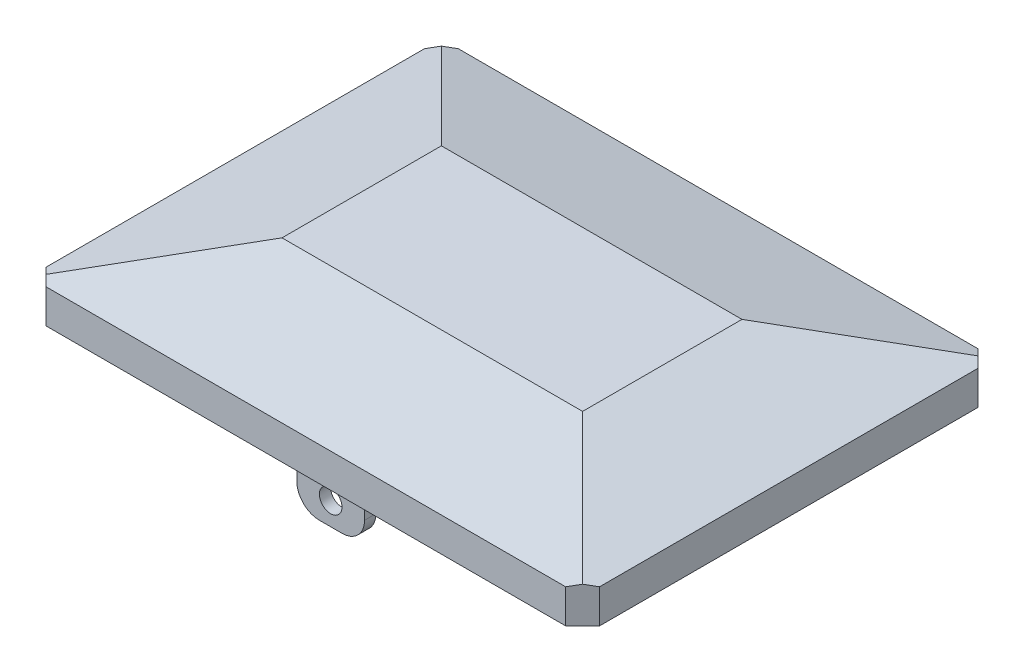
SolidWorks part; units mm, degrees
material "ABS PC"
ref_plane "Front Plane" through (0, 0, 0) normal (0, 0, 1) x (1, 0, 0)
ref_plane "Top Plane" through (0, 0, 0) normal (0, 1, 0) x (1, 0, 0)
ref_plane "Right Plane" through (0, 0, 0) normal (1, 0, 0) x (0, 0, -1)
sketch "Sketch1" plane through (0, 0, 0) normal (0, 1, 0) x (1, 0, 0)
  line L1 (-12.25, 9.125) -> (12.25, 9.125)
  line L2 (-12.25, 9.125) -> (-12.25, -9.125)
  line L3 (-12.25, -9.125) -> (12.25, -9.125)
  line L4 (12.25, 9.125) -> (12.25, -9.125)
  line L5 (-12.25, 9.125) -> (12.25, -9.125) construction
  line L6 (-12.25, -9.125) -> (12.25, 9.125) construction
  point P0 (0, 0)
  dimension "D1" = 24.5
  dimension "D2" = 18.25
extrude "Boss-Extrude1" add sketch "Sketch1" along normal blind 3
chamfer "Chamfer1" distance 0.75 angle 45 4 edges at (-12.25, 1.5, -9.125) (12.25, 1.5, -9.125) (12.25, 1.5, 9.125) (-12.25, 1.5, 9.125)
chamfer "Chamfer2" distance 1.5 angle 75 4 edges at (12.25, 3, 0) (0, 3, 9.125) (-12.25, 3, 0) (0, 3, -9.125)
sketch "Sketch4" plane through (0, 0, 0) normal (0, -1, 0) x (1, 0, 0)
  line L0 (-1.5, 8.025) -> (1.5, 8.025)
  line L2 (1.5, 8.025) -> (1.5, 7.525)
  line L3 (1.5, 7.525) -> (-1.5, 7.525)
  line L4 (-1.5, 7.525) -> (-1.5, 8.025)
  line L5 (0, -1.65) -> (0, 1.65) construction
  line L6 (-11.5, 9.125) -> (11.5, 9.125) construction
  dimension "D1" = 1.5
  dimension "D2" = 1.5
  dimension "D3" = 0.5
  dimension "D4" = 1.1
extrude "Boss-Extrude2" add sketch "Sketch4" along normal blind 2.5
fillet "Fillet2" radius 1 2 edges at (-1.5, -2.5, 7.775) (1.5, -2.5, 7.775)
mirror "Mirror2" about plane through (0, 0, 0) normal (0, 0, 1) of "Fillet2", "Boss-Extrude2"
sketch "Sketch5" plane through (0, 0, -8.025) normal (0, 0, -1) x (-1, 0, 0)
  line L0 (0, 1.65) -> (0, -1.65) construction
  line L1 (10.0375, 0) -> (-10.0375, 0) construction
  circle A0 centre (0, -1.5) radius 0.75
  dimension "D1" = 1.5
extrude "Boss-Extrude3" add sketch "Sketch5" along normal blind 0.5
sketch "Sketch6" plane through (0, 0, 8.025) normal (0, 0, 1) x (1, 0, 0)
  line L0 (0, -1.65) -> (0, 1.65) construction
  line L1 (1.5, 0) -> (-1.5, 0) construction
  circle A0 centre (0, -1.5) radius 0.5
  dimension "D1" = 1
  dimension "D2" = 1.5
extrude "Cut-Extrude2" cut sketch "Sketch6" against normal up to next
